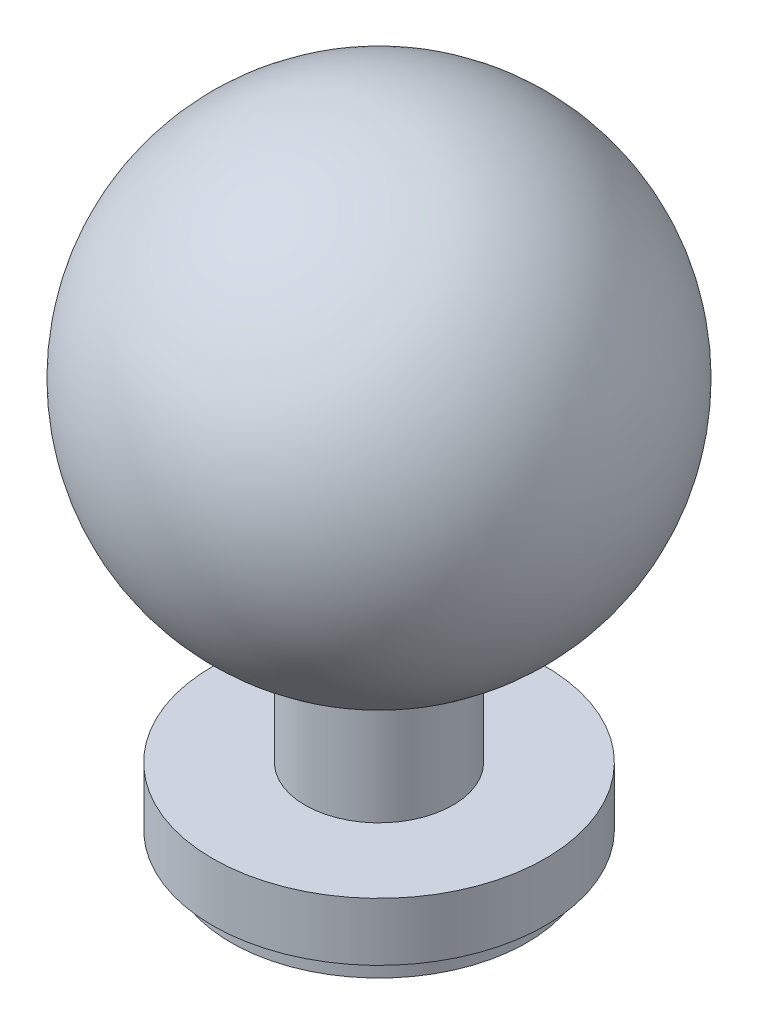
SolidWorks part; units mm, degrees
ref_plane "Front Plane" through (0, 0, 0) normal (0, 0, 1) x (1, 0, 0)
ref_plane "Top Plane" through (0, 0, 0) normal (0, 1, 0) x (1, 0, 0)
ref_plane "Right Plane" through (0, 0, 0) normal (1, 0, 0) x (0, 0, -1)
sketch "Sketch1" plane through (0, 0, 0) normal (0, 1, 0) x (1, 0, 0)
  circle A0 centre (0, 0) radius 4.5
  dimension "D1" = 9
extrude "Boss-Extrude1" add sketch "Sketch1" along normal blind 1.57
sketch "Sketch2" plane through (0, 1.57, 0) normal (0, 1, 0) x (1, 0, 0)
  circle A0 centre (0, 0) radius 2
  dimension "D1" = 4
extrude "Boss-Extrude2" add sketch "Sketch2" along normal blind 9
sketch "Sketch3" plane through (0, 10.57, 0) normal (0, 1, 0) x (1, 0, 0)
  line L0 (0, 8.312) -> (0, -16.0573) construction
  line L1 (0, 6.35) -> (0, -6.35)
  arc A0 (0, -6.35) -> (0, 6.35) centre (0, 0) ccw
  dimension "D1" = 6.35
revolve "Revolve1" add sketch "Sketch3" angle 360 about L0
sketch "Sketch4" plane through (0, 0, 0) normal (0, -1, 0) x (1, 0, 0)
  circle A0 centre (0, 0) radius 4
  dimension "D1" = 8
extrude "Boss-Extrude3" add sketch "Sketch4" along normal blind 0.65
ref_point "Point1"
ref_plane "Plane1" through (0, 16.92, 0) normal (0, 1, 0) x (1, 0, 0)
